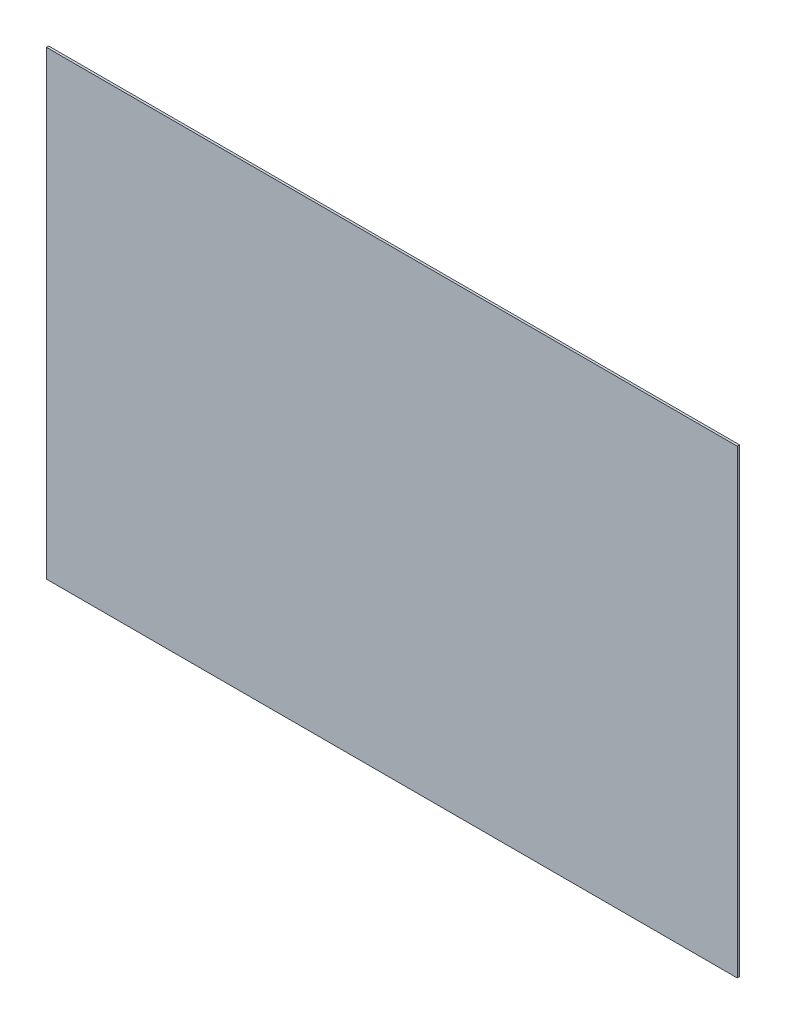
SolidWorks part; units mm, degrees
ref_plane "前视基准面" through (0, 0, 0) normal (0, 0, 1) x (1, 0, 0)
ref_plane "上视基准面" through (0, 0, 0) normal (0, 1, 0) x (1, 0, 0)
ref_plane "右视基准面" through (0, 0, 0) normal (1, 0, 0) x (0, 0, -1)
sketch "草图1" plane through (0, 0, 0) normal (0, 0, 1) x (1, 0, 0)
  line L1 (-150, 100) -> (150, 100)
  line L2 (-150, 100) -> (-150, -100)
  line L3 (-150, -100) -> (150, -100)
  line L4 (150, 100) -> (150, -100)
  line L5 (-150, 100) -> (150, -100) construction
  line L6 (-150, -100) -> (150, 100) construction
  point P0 (0, 0)
  dimension "D1" = 200
  dimension "D2" = 300
extrude "凸台-拉伸1" add sketch "草图1" along normal blind 1
